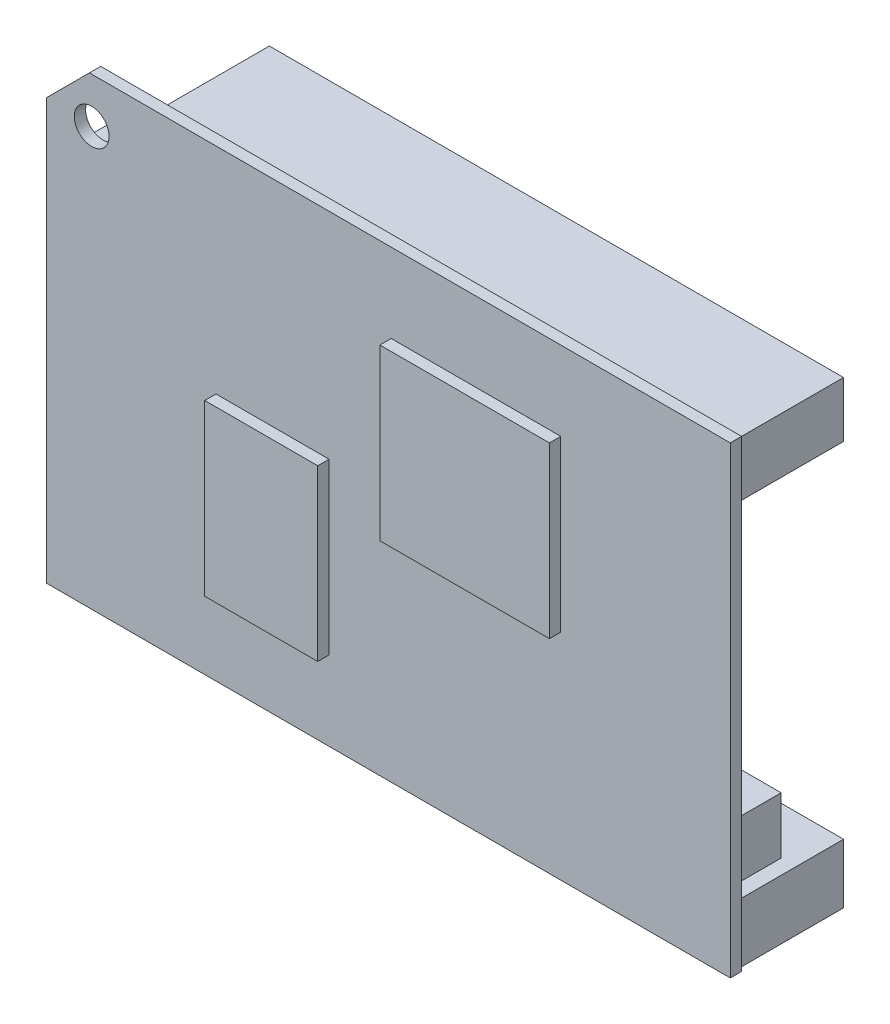
SolidWorks part; units mm, degrees
ref_plane "Front Plane" through (0, 0, 0) normal (0, 0, 1) x (1, 0, 0)
ref_plane "Top Plane" through (0, 0, 0) normal (0, 1, 0) x (1, 0, 0)
ref_plane "Right Plane" through (0, 0, 0) normal (1, 0, 0) x (0, 0, -1)
sketch "Sketch1" plane through (0, 0, 0) normal (0, 0, 1) x (1, 0, 0)
  line L0 (-56.7, 0) -> (-60.5, -3.8)
  line L1 (0, 0) -> (-60.5, 0)
  line L2 (0, 0) -> (0, -41)
  line L3 (0, -41) -> (-60.5, -41)
  line L4 (-60.5, 0) -> (-60.5, -41)
  circle A0 centre (-56.5, -4) radius 1.54
  dimension "D5" = 4
  dimension "D6" = 4
  dimension "D7" = 3.08
  dimension "D1" = 41
  dimension "D2" = 60.5
  dimension "D3" = 3.8
  dimension "D4" = 3.8
extrude "Boss-Extrude1" add sketch "Sketch1" along normal blind 1 contours L0 L4 L3 L2 L1 A0
sketch "Sketch2" plane through (0, 0, 0) normal (0, 0, -1) x (-1, 0, 0)
  line L0 (0, 0) -> (0, -41) construction
  line L1 (30, -22) -> (15, -22)
  line L2 (30, -22) -> (30, -7)
  line L3 (30, -7) -> (15, -7)
  line L4 (15, -22) -> (15, -7)
  line L6 (0, 0) -> (56.7, 0) construction
  dimension "D1" = 15
  dimension "D2" = 15
  dimension "D3" = 15
  dimension "D4" = 7
extrude "Boss-Extrude2" add sketch "Sketch2" against normal blind 2
sketch "Sketch3" plane through (0, 0, 0) normal (0, 0, -1) x (-1, 0, 0)
  line L1 (45.5, -34) -> (35.5, -34)
  line L2 (45.5, -34) -> (45.5, -19)
  line L3 (45.5, -19) -> (35.5, -19)
  line L4 (35.5, -34) -> (35.5, -19)
  line L5 (60.5, -3.8) -> (60.5, -41) construction
  line L6 (0, -41) -> (60.5, -41) construction
  dimension "D1" = 15
  dimension "D2" = 10
  dimension "D3" = 7
  dimension "D4" = 15
extrude "Boss-Extrude3" add sketch "Sketch3" against normal blind 2
sketch "Sketch4" plane through (0, 0, 0) normal (0, 0, -1) x (-1, 0, 0)
  line L0 (0, -41) -> (60.5, -41) construction
  line L1 (50.98, -40.82) -> (0.18, -40.82)
  line L2 (50.98, -40.82) -> (50.98, -35.56)
  line L3 (50.98, -35.56) -> (0.18, -35.56)
  line L4 (0.18, -40.82) -> (0.18, -35.56)
  line L5 (50.98, -5.08) -> (0.18, -5.08)
  line L6 (50.98, -5.08) -> (50.98, -0.18)
  line L7 (50.98, -0.18) -> (0.18, -0.18)
  line L8 (0.18, -5.08) -> (0.18, -0.18)
  line L9 (0, 0) -> (56.7, 0) construction
  line L10 (0, 0) -> (0, -41) construction
  dimension "D1" = 0.18
  dimension "D2" = 0.18
  dimension "D3" = 30.48
  dimension "D4" = 50.8
  dimension "D5" = 50.8
  dimension "D6" = 0.18
  dimension "D7" = 0.18
  dimension "D8" = 5.26
extrude "Boss-Extrude4" add sketch "Sketch4" along normal blind 9.2
sketch "Sketch5" plane through (0, 0, 0) normal (0, 0, -1) x (-1, 0, 0)
  line L0 (60.5, -3.8) -> (60.5, -41) construction
  line L1 (60.5, -20.08) -> (45.5, -20.08)
  line L2 (60, -20.08) -> (60, -8.08)
  line L3 (60.5, -8.08) -> (45.5, -8.08)
  line L4 (45.5, -20.08) -> (45.5, -8.08)
  line L5 (0.18, -5.08) -> (50.98, -5.08) construction
  line L8 (60, -20.08) -> (45.5, -20.08)
  line L9 (60, -20.08) -> (60, -8.08)
  line L10 (60, -8.08) -> (45.5, -8.08)
  line L11 (45.5, -20.08) -> (45.5, -8.08)
  dimension "D1" = 15
  dimension "D2" = 12
  dimension "D3" = 3
  dimension "D4" = 0.5
extrude "Boss-Extrude6" add sketch "Sketch5" along normal blind 7 contours L4 L1 L2 L3
sketch "Sketch6" plane through (0, 0, 0) normal (0, 0, -1) x (-1, 0, 0)
  line L0 (60, -20.08) -> (45.5, -20.08) construction
  line L1 (45.5, -23.08) -> (57.5, -23.08)
  line L2 (45.5, -23.08) -> (45.5, -28.08)
  line L3 (45.5, -28.08) -> (57.5, -28.08)
  line L4 (57.5, -23.08) -> (57.5, -28.08)
  line L5 (45.5, -20.08) -> (45.5, -8.08) construction
  dimension "D1" = 3
  dimension "D2" = 5
  dimension "D3" = 0
  dimension "D4" = 12
extrude "Boss-Extrude7" add sketch "Sketch6" along normal blind 5
sketch "Sketch7" plane through (-57.5, 0, 0) normal (-1, 0, 0) x (0, 0, 1)
  line L0 (-5, -23.08) -> (0, -23.08) construction
  line L1 (-5, -28.08) -> (-5, -23.08) construction
  circle A0 centre (-2.5, -25.58) radius 2.25
  dimension "D1" = 4.5
  dimension "D2" = 2.5
  dimension "D3" = 2.5
extrude "Boss-Extrude8" add sketch "Sketch7" along normal blind 2
sketch "Sketch8" plane through (0, 0, 0) normal (0, 0, -1) x (-1, 0, 0)
  line L0 (45.5, -28.08) -> (57.5, -28.08) construction
  line L1 (60, -33.08) -> (54, -33.08)
  line L2 (60, -33.08) -> (60, -40)
  line L3 (60, -40) -> (54, -40)
  line L4 (54, -33.08) -> (54, -40)
  line L5 (0, -41) -> (60.5, -41) construction
  line L6 (60.5, -3.8) -> (60.5, -41) construction
  dimension "D1" = 5
  dimension "D2" = 1
  dimension "D3" = 6
  dimension "D4" = 0.5
extrude "Boss-Extrude9" add sketch "Sketch8" along normal blind 4
sketch "Sketch9" plane through (0, 0, 0) normal (0, 0, -1) x (-1, 0, 0)
  line L0 (50.98, -35.56) -> (0.18, -35.56) construction
  line L1 (6.5, -34.56) -> (0.5, -34.56)
  line L2 (6.5, -34.56) -> (6.5, -29.56)
  line L3 (6.5, -29.56) -> (0.5, -29.56)
  line L4 (0.5, -34.56) -> (0.5, -29.56)
  line L5 (0, 0) -> (0, -41) construction
  dimension "D1" = 1
  dimension "D2" = 5
  dimension "D3" = 6
  dimension "D4" = 0.5
extrude "Boss-Extrude10" add sketch "Sketch9" along normal blind 4
sketch "Sketch10" plane through (0, 0, 0) normal (0, 0, -1) x (-1, 0, 0)
  line L0 (50.98, -35.56) -> (0.18, -35.56) construction
  line L1 (32, -28.56) -> (20, -28.56)
  line L2 (32, -28.56) -> (32, -10.08)
  line L3 (32, -10.08) -> (20, -10.08)
  line L4 (20, -28.56) -> (20, -10.08)
  line L5 (0.18, -5.08) -> (50.98, -5.08) construction
  line L6 (0, 0) -> (0, -41) construction
  dimension "D1" = 7
  dimension "D2" = 5
  dimension "D3" = 12
  dimension "D4" = 20
extrude "Boss-Extrude11" add sketch "Sketch10" along normal blind 1
sketch "Sketch11" plane through (0, 0, 0) normal (0, 0, -1) x (-1, 0, 0)
  line L0 (0.18, -5.08) -> (50.98, -5.08) construction
  line L1 (16, -18.08) -> (4, -18.08)
  line L2 (16, -18.08) -> (16, -6.08)
  line L3 (16, -6.08) -> (4, -6.08)
  line L4 (4, -18.08) -> (4, -6.08)
  line L5 (0, 0) -> (0, -41) construction
  dimension "D1" = 12
  dimension "D2" = 12
  dimension "D3" = 1
  dimension "D4" = 4
extrude "Boss-Extrude12" add sketch "Sketch11" along normal blind 1
sketch "Sketch12" plane through (0, 0, -1) normal (0, 0, -1) x (-1, 0, 0)
  line L0 (4, -18.08) -> (16, -18.08) construction
  line L1 (12, -13.08) -> (8, -13.08)
  line L2 (12, -13.08) -> (12, -9.08)
  line L3 (12, -9.08) -> (8, -9.08)
  line L4 (8, -13.08) -> (8, -9.08)
  line L5 (16, -6.08) -> (4, -6.08) construction
  line L6 (16, -18.08) -> (16, -6.08) construction
  line L7 (4, -6.08) -> (4, -18.08) construction
  dimension "D1" = 5
  dimension "D2" = 3
  dimension "D3" = 4
  dimension "D4" = 4
extrude "Boss-Extrude13" add sketch "Sketch12" along normal blind 1
sketch "Sketch13" plane through (0, 0, 0) normal (0, 0, -1) x (-1, 0, 0)
  line L0 (16, -6.08) -> (4, -6.08) construction
  line L1 (3, -6.08) -> (1, -6.08)
  line L2 (3, -6.08) -> (3, -11.08)
  line L3 (3, -11.08) -> (1, -11.08)
  line L4 (1, -6.08) -> (1, -11.08)
  line L5 (4, -6.08) -> (4, -18.08) construction
  line L6 (0, 0) -> (0, -41) construction
  dimension "D1" = 0
  dimension "D2" = 1
  dimension "D3" = 1
  dimension "D4" = 5
extrude "Boss-Extrude14" add sketch "Sketch13" along normal blind 0.5
sketch "Sketch14" plane through (0, 0, -0.5) normal (0, 0, -1) x (-1, 0, 0)
  line L0 (1, -11.08) -> (3, -11.08) construction
  line L1 (3, -6.08) -> (1, -6.08) construction
  circle A0 centre (2.0374, -8.5803) radius 0.75
  point P4 (2, -11.08)
  dimension "D1" = 2.5
  dimension "D3" = 1.5
  dimension "D2" = 2.5003
extrude "Boss-Extrude15" add sketch "Sketch14" along normal blind 0.5
